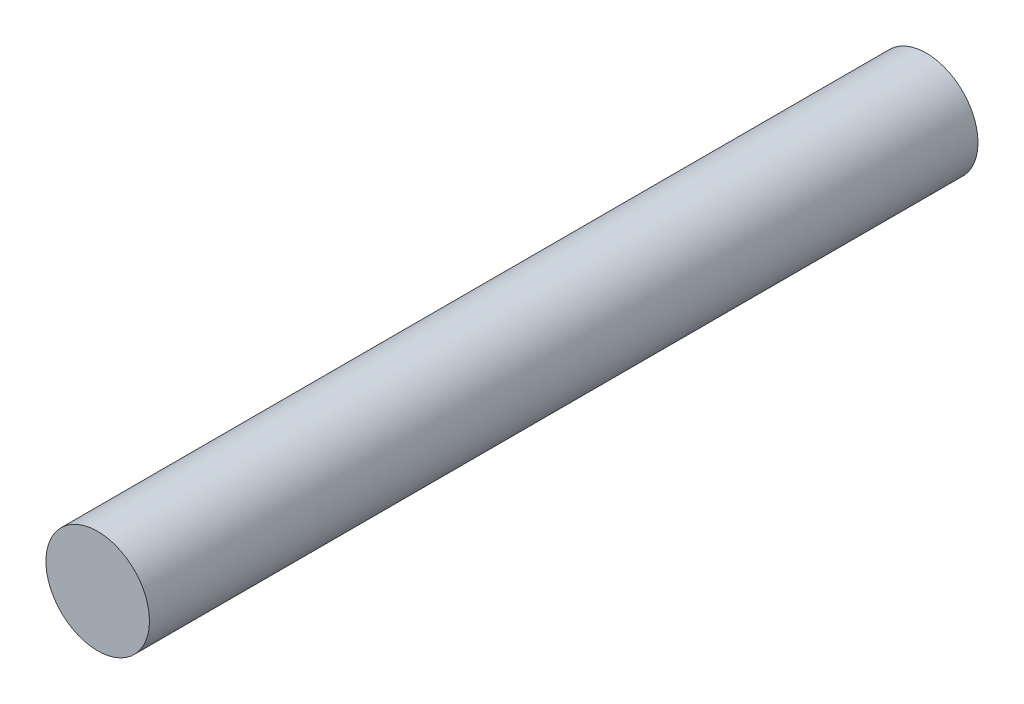
SolidWorks part; units mm, degrees
material "1023 Carbon Steel Sheet (SS)"
ref_plane "Front Plane" through (0, 0, 0) normal (0, 0, 1) x (1, 0, 0)
ref_plane "Top Plane" through (0, 0, 0) normal (0, 1, 0) x (1, 0, 0)
ref_plane "Right Plane" through (0, 0, 0) normal (1, 0, 0) x (0, 0, -1)
sketch "Sketch1" plane through (0, 0, 0) normal (0, 0, 1) x (1, 0, 0)
  circle A0 centre (0, 0) radius 1
  dimension "D1" = 2
extrude "Boss-Extrude1" add sketch "Sketch1" along normal blind 16
